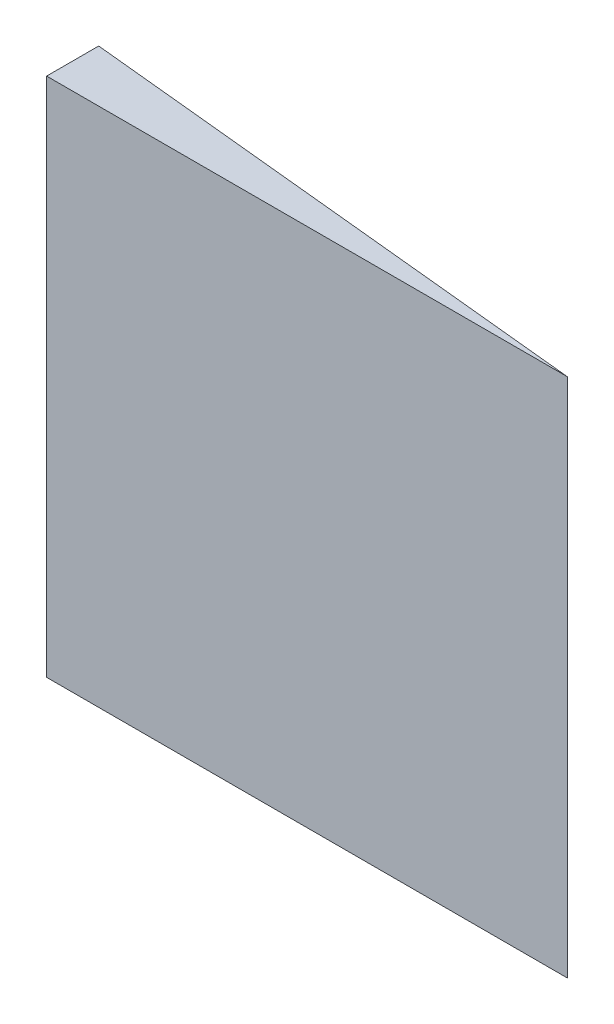
SolidWorks part; units mm, degrees
ref_plane "前视基准面" through (0, 0, 0) normal (0, 0, 1) x (1, 0, 0)
ref_plane "上视基准面" through (0, 0, 0) normal (0, 1, 0) x (1, 0, 0)
ref_plane "右视基准面" through (0, 0, 0) normal (1, 0, 0) x (0, 0, -1)
sketch "草图2" plane through (0, 0, 0) normal (0, 1, 0) x (1, 0, 0)
  line L0 (0, 0) -> (1000, 0)
  line L5 (1000, 0) -> (0, 100)
  line L6 (0, 100) -> (0, 0)
  dimension "D1" = 100
  dimension "D2" = 1000
extrude "凸台-拉伸2" add sketch "草图2" along normal blind 1000 contours L5 L6 L0
